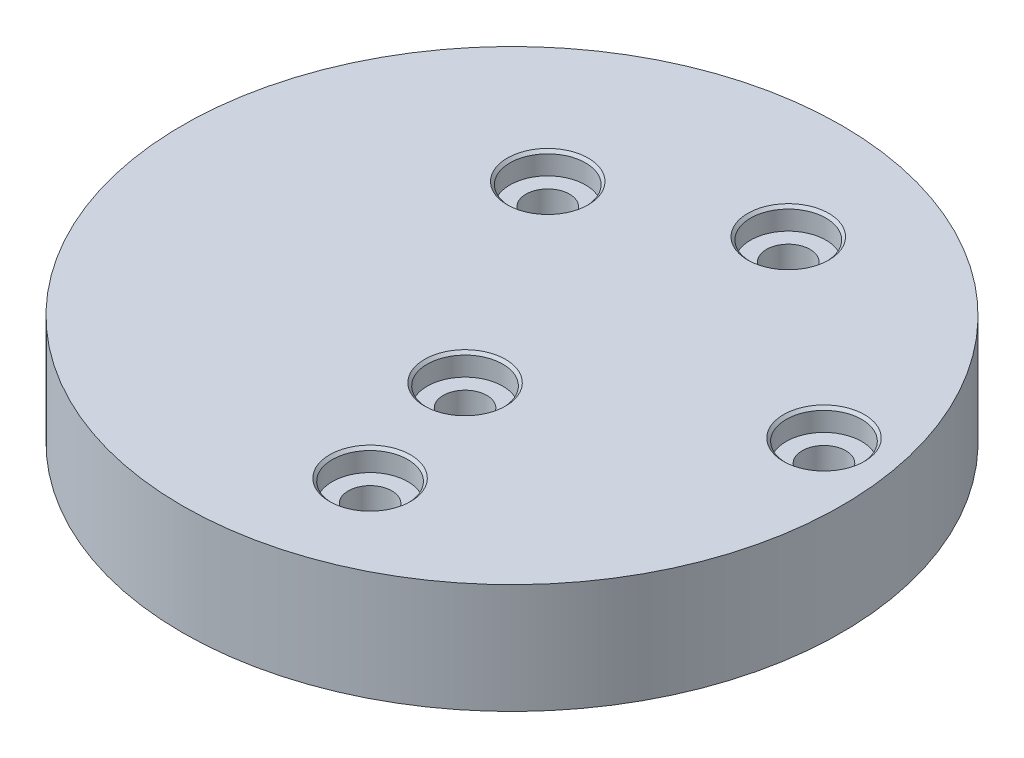
SolidWorks part; units mm, degrees
ref_plane "Front Plane" through (0, 0, 0) normal (0, 0, 1) x (1, 0, 0)
ref_plane "Top Plane" through (0, 0, 0) normal (0, 1, 0) x (1, 0, 0)
ref_plane "Right Plane" through (0, 0, 0) normal (1, 0, 0) x (0, 0, -1)
sketch "Sketch1" plane through (0, 0, 0) normal (0, 1, 0) x (1, 0, 0)
  circle A0 centre (0, 0) radius 76.2
  dimension "D1" = 152.4
extrude "Boss-Extrude1" add sketch "Sketch1" against normal blind 25.4
sketch "Sketch2" plane through (0, 0, 0) normal (0, 1, 0) x (1, 0, 0)
  line L1 (-50.8, -38.1) -> (50.8, -38.1)
  line L2 (-50.8, -38.1) -> (-50.8, 38.1)
  line L3 (-50.8, 38.1) -> (50.8, 38.1)
  line L4 (50.8, -38.1) -> (50.8, 38.1)
  line L5 (-50.8, -38.1) -> (50.8, 38.1) construction
  line L6 (-50.8, 38.1) -> (50.8, -38.1) construction
  point P0 (0, 0)
  dimension "D1" = 76.2
  dimension "D2" = 101.6
hole_wizard "CBORE for 3/8 Button Head Cap Screw1" positions "Sketch3" profile "Sketch4" counterbore size "3/8" standard "ANSI Inch" end condition through all
sketch "Sketch3" plane through (0, 0, 0) normal (0, 1, 0) x (1, 0, 0)
  point P2 (60.5813, 11.5529)
  point P4 (16.1466, -48.9641)
  point P6 (8.0149, -18.8719)
  point P10 (-22.7229, 30.9885)
  point P16 (16.1466, 47.7341)
sketch "Sketch4" plane through (60.5813, 0, -11.5529) normal (1, 0, 0) x (0, 0, 1)
  line L0 (0, 0) -> (0, 25.4)
  line L1 (0, 25.4) -> (5.0419, 25.4)
  line L3 (5.0419, 25.4) -> (5.0419, 5.0546)
  line L4 (8.7312, 5.0546) -> (5.0419, 5.0546)
  line L5 (8.7312, 5.0546) -> (8.7312, 0.635)
  line L6 (8.7312, 0.635) -> (9.3662, 0)
  line L7 (9.3662, 0) -> (0, 0)
  line L8 (-8.7312, 0.635) -> (-9.3662, 0) construction
  line L11 (0, -6.35) -> (0, 107.95) construction
  dimension "Thru Hole Dia." = 10.0838
  dimension "Thru Hole Depth" = 25.4
  dimension "C'Bore Dia." = 17.4625
  dimension "C'Bore Depth" = 5.0546
  dimension "Near C'Sink Dia." = 18.7325
  dimension "Near C'Sink Angle" = 90
